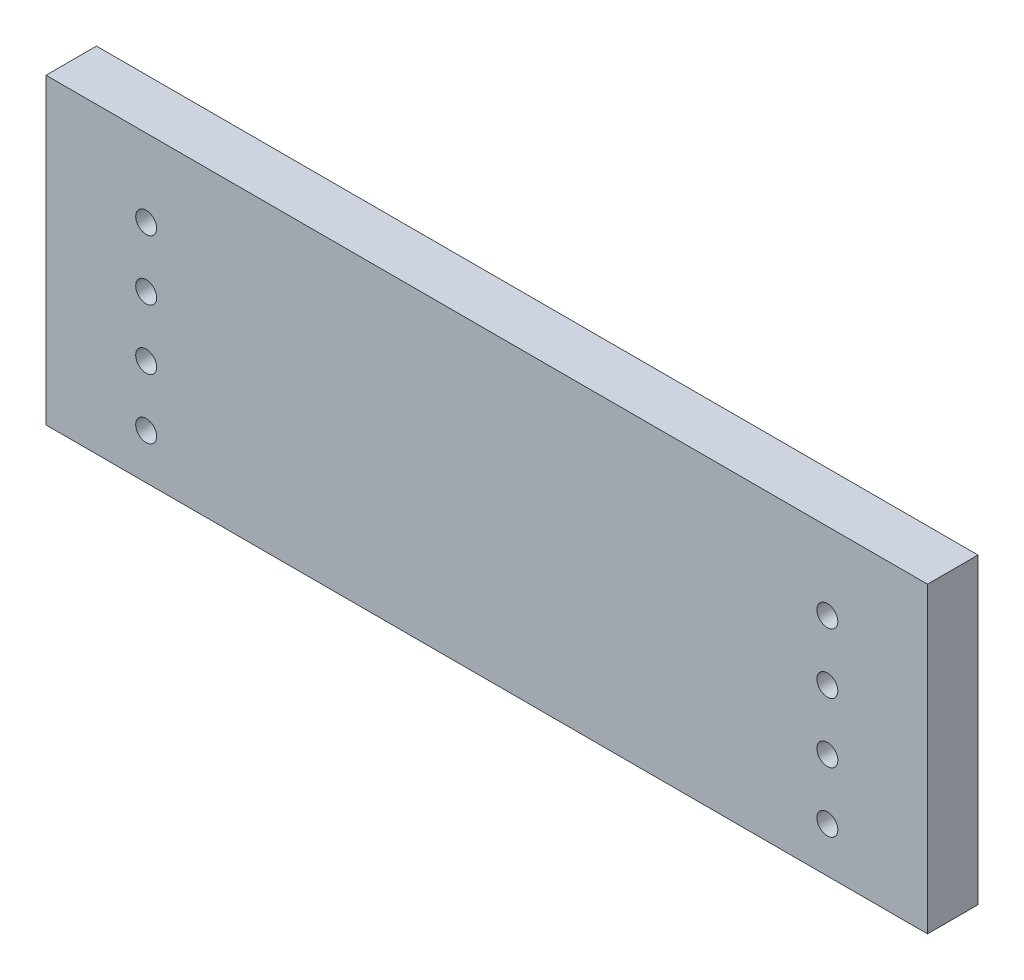
SolidWorks part; units mm, degrees
ref_plane "Front Plane" through (0, 0, 0) normal (0, 0, 1) x (1, 0, 0)
ref_plane "Top Plane" through (0, 0, 0) normal (0, 1, 0) x (1, 0, 0)
ref_plane "Right Plane" through (0, 0, 0) normal (1, 0, 0) x (0, 0, -1)
sketch "Sketch1" plane through (0, 0, 0) normal (1, 0, 0) x (0, 0, -1)
  line L1 (-6, -36) -> (6, -36)
  line L2 (-6, -36) -> (-6, 36)
  line L3 (-6, 36) -> (6, 36)
  line L4 (6, -36) -> (6, 36)
  line L5 (-6, -36) -> (6, 36) construction
  line L6 (-6, 36) -> (6, -36) construction
  point P0 (0, 0)
  dimension "D1" = 12
  dimension "D2" = 72
extrude "Boss-Extrude1" add sketch "Sketch1" along normal mid plane 209.55
sketch "Sketch2" plane through (0, 0, 6) normal (0, 0, 1) x (1, 0, 0)
  line L0 (-76.2, 36) -> (-76.2, -36) construction
  line L1 (104.775, 36) -> (-104.775, 36) construction
  line L2 (104.775, -36) -> (-104.775, -36) construction
  line L3 (-104.775, 36) -> (-104.775, -36) construction
  line L4 (-80.9625, 36) -> (-80.9625, -36) construction
  line L5 (-80.9625, -25.2375) -> (-80.9625, -10.95) construction
  line L6 (0, 0) -> (0, 36) construction
  point P10 (-80.9625, -25.2375)
  point P12 (80.9625, 17.625)
  point P13 (-80.9625, -10.95)
  point P14 (-80.9625, 3.3375)
  point P15 (-80.9625, 17.625)
  point P20 (80.9625, 3.3375)
  point P21 (80.9625, -10.95)
  point P22 (80.9625, -25.2375)
  dimension "D1" = 28.575
  dimension "D2" = 4.7625
  dimension "D3" = 10.7625
  dimension "D5" = 14.2875
  dimension "D4" = 4
hole_wizard "CBORE for #10 Button Head Cap Screw1" positions "Sketch3" profile "Sketch4" counterbore size "#10" standard "ANSI Inch" end condition through all
sketch "Sketch3" plane through (0, 0, -6) normal (0, 0, 1) x (1, 0, 0)
  point P0 (-80.9625, -25.2375)
  point P3 (-80.9625, -10.95)
  point P6 (-80.9625, 3.3375)
  point P9 (-80.9625, 17.625)
  point P12 (80.9625, -25.2375)
  point P15 (80.9625, -10.95)
  point P18 (80.9625, 3.3375)
  point P21 (80.9625, 17.625)
sketch "Sketch4" plane through (-80.9625, -25.2375, -6) normal (1, 0, 0) x (0, 1, 0)
  line L0 (0, 0) -> (0, 12)
  line L1 (0, 12) -> (2.4892, 12)
  line L3 (2.4892, 12) -> (2.4892, 2.5654)
  line L4 (2.4892, 2.5654) -> (4.9606, 2.5654)
  line L5 (4.9606, 2.5654) -> (4.9606, 0)
  line L7 (4.9606, 0) -> (0, 0)
  line L11 (0, -6.35) -> (0, 107.95) construction
  dimension "Thru Hole Dia." = 4.9784
  dimension "Thru Hole Depth" = 12
  dimension "C'Bore Dia." = 9.9212
  dimension "C'Bore Depth" = 2.5654
sketch "Sketch5" plane through (0, 0, -6) normal (0, 0, -1) x (-1, 0, 0)
  line L0 (104.775, -36) -> (104.775, 36) construction
  line L1 (-104.775, 36) -> (104.775, 36) construction
  circle A0 centre (64.15, 10) radius 5.25
  circle A1 centre (50.15, 10) radius 5.25
  point P8 (0, 0)
  point P9 (0, 0)
  dimension "D3" = 10.5
  dimension "D5" = 10.5
  dimension "D1" = 40.625
  dimension "D2" = 26
  dimension "D4" = 14
extrude "Cut-Extrude1" cut sketch "Sketch5" against normal blind 3.5
equation "\"D1@Boss-Extrude1\"=8.25in"
equation "\"D1@Sketch2\"=0.75in + 0.375in"
equation "\"D2@Sketch2\"=0.375in/2"
equation "\"D3@Sketch2\"=0.375in/2 + 6mm"
